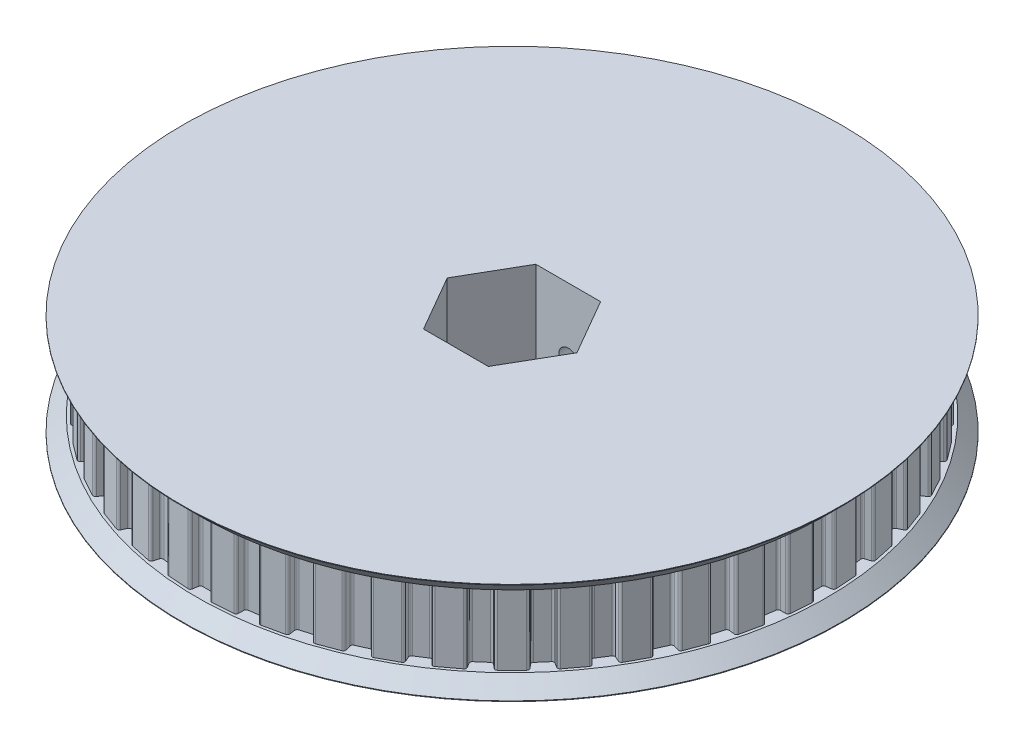
SolidWorks part; units mm, degrees
ref_plane "Front Plane" through (0, 0, 0) normal (0, 0, 1) x (1, 0, 0)
ref_plane "Top Plane" through (0, 0, 0) normal (0, 1, 0) x (1, 0, 0)
ref_plane "Right Plane" through (0, 0, 0) normal (1, 0, 0) x (0, 0, -1)
sketch "Sketch1" plane through (0, 0, 0) normal (0, 1, 0) x (1, 0, 0)
  line L0 (-1.778, 64.4158) -> (1.778, 64.4158) construction
  line L12 (-1.778, 64.4158) -> (-2.0983, 66.4224) construction
  line L13 (1.778, 64.4158) -> (2.0983, 66.4224) construction
  line L14 (2.0983, 66.4224) -> (-2.0983, 66.4224) construction
  line L15 (-2.0983, 66.4224) -> (-7.376, 66.045) construction
  line L16 (2.0983, 66.4224) -> (7.376, 66.045) construction
  line L17 (7.376, 66.045) -> (7.4074, 64.0132) construction
  line L18 (7.4074, 64.0132) -> (10.9272, 63.5071) construction
  line L19 (10.9272, 63.5071) -> (11.5298, 65.4477) construction
  line L20 (11.5298, 65.4477) -> (7.376, 66.045) construction
  line L21 (0, 64.4158) -> (0, 66.4224) construction
  line L22 (9.1673, 63.7602) -> (9.4529, 65.7464) construction
  line L105 (-1.3447, 64.4158) -> (1.3447, 64.4158)
  line L106 (1.8463, 64.8438) -> (2.0249, 65.9626)
  line L107 (2.5628, 66.3892) -> (6.9115, 66.0782)
  line L108 (7.3832, 65.5793) -> (7.4007, 64.4465)
  line L109 (7.8364, 63.9515) -> (10.4983, 63.5688)
  line L110 (11.0557, 63.921) -> (11.3917, 65.003)
  line L112 (9.4529, 65.7464) -> (10.0269, 69.7388) construction
  line L113 (0, 66.4224) -> (0, 66.7018) construction
  line L117 (-6.9115, 66.0782) -> (-2.5628, 66.3892)
  line L118 (-2.0249, 65.9626) -> (-1.8463, 64.8438)
  line L119 (28.6165, 58.217) -> (29.2437, 59.1605)
  line L120 (25.5362, 59.1533) -> (27.9824, 58.0361)
  line L121 (25.5599, 60.8428) -> (25.2576, 59.7509)
  line L122 (21.163, 62.978) -> (25.2479, 61.4544)
  line L123 (20.0401, 61.697) -> (20.5267, 62.7202)
  line L124 (16.8579, 62.1854) -> (19.4382, 61.4277)
  line L125 (16.6409, 63.8611) -> (16.4971, 62.7373)
  line L126 (11.9849, 65.3487) -> (16.245, 64.422)
  line L127 (43.859, 47.7966) -> (44.7266, 48.5252)
  line L128 (41.1672, 49.5628) -> (43.1996, 47.8017)
  line L129 (41.666, 51.1772) -> (41.0683, 50.2147)
  line L130 (38.0487, 54.4646) -> (41.5389, 51.8519)
  line L131 (36.6104, 53.5519) -> (37.3655, 54.3965)
  line L132 (33.6946, 54.917) -> (35.957, 53.4631)
  line L133 (33.9586, 56.586) -> (33.504, 55.5482)
  line L134 (29.9103, 59.3251) -> (33.7368, 57.2357)
  line L135 (55.5482, 33.504) -> (56.586, 33.9586)
  line L136 (53.4631, 35.957) -> (54.917, 33.6946)
  line L137 (54.3965, 37.3655) -> (53.5519, 36.6104)
  line L138 (51.8519, 41.5389) -> (54.4646, 38.0487)
  line L139 (50.2147, 41.0683) -> (51.1772, 41.666)
  line L140 (47.8017, 43.1996) -> (49.5628, 41.1672)
  line L141 (48.5252, 44.7266) -> (47.7966, 43.859)
  line L142 (45.4125, 48.4954) -> (48.4954, 45.4125)
  line L143 (62.7373, 16.4971) -> (63.8611, 16.6409)
  line L144 (61.4277, 19.4382) -> (62.1854, 16.8579)
  line L145 (62.7202, 20.5267) -> (61.697, 20.0401)
  line L146 (61.4544, 25.2479) -> (62.978, 21.163)
  line L147 (59.7509, 25.2576) -> (60.8428, 25.5599)
  line L148 (58.0361, 27.9824) -> (59.1533, 25.5362)
  line L149 (59.1605, 29.2437) -> (58.217, 28.6165)
  line L150 (57.2357, 33.7368) -> (59.3251, 29.9103)
  line L151 (64.8438, -1.8463) -> (65.9626, -2.0249)
  line L152 (64.4158, 1.3447) -> (64.4158, -1.3447)
  line L153 (65.9626, 2.0249) -> (64.8438, 1.8463)
  line L154 (66.0782, 6.9115) -> (66.3892, 2.5628)
  line L155 (64.4465, 7.4007) -> (65.5793, 7.3832)
  line L156 (63.5688, 10.4983) -> (63.9515, 7.8364)
  line L157 (65.003, 11.3917) -> (63.921, 11.0557)
  line L158 (64.422, 16.245) -> (65.3487, 11.9849)
  line L159 (61.697, -20.0401) -> (62.7202, -20.5267)
  line L160 (62.1854, -16.8579) -> (61.4277, -19.4382)
  line L161 (63.8611, -16.6409) -> (62.7373, -16.4971)
  line L162 (65.3487, -11.9849) -> (64.422, -16.245)
  line L163 (63.921, -11.0557) -> (65.003, -11.3917)
  line L164 (63.9515, -7.8364) -> (63.5688, -10.4983)
  line L165 (65.5793, -7.3832) -> (64.4465, -7.4007)
  line L166 (66.3892, -2.5628) -> (66.0782, -6.9115)
  line L167 (53.5519, -36.6104) -> (54.3965, -37.3655)
  line L168 (54.917, -33.6946) -> (53.4631, -35.957)
  line L169 (56.586, -33.9586) -> (55.5482, -33.504)
  line L170 (59.3251, -29.9103) -> (57.2357, -33.7368)
  line L171 (58.217, -28.6165) -> (59.1605, -29.2437)
  line L172 (59.1533, -25.5362) -> (58.0361, -27.9824)
  line L173 (60.8428, -25.5599) -> (59.7509, -25.2576)
  line L174 (62.978, -21.163) -> (61.4544, -25.2479)
  line L175 (41.0683, -50.2147) -> (41.666, -51.1772)
  line L176 (43.1996, -47.8017) -> (41.1672, -49.5628)
  line L177 (44.7266, -48.5252) -> (43.859, -47.7966)
  line L178 (48.4954, -45.4125) -> (45.4125, -48.4954)
  line L179 (47.7966, -43.859) -> (48.5252, -44.7266)
  line L180 (49.5628, -41.1672) -> (47.8017, -43.1996)
  line L181 (51.1772, -41.666) -> (50.2147, -41.0683)
  line L182 (54.4646, -38.0487) -> (51.8519, -41.5389)
  line L183 (25.2576, -59.7509) -> (25.5599, -60.8428)
  line L184 (27.9824, -58.0361) -> (25.5362, -59.1533)
  line L185 (29.2437, -59.1605) -> (28.6165, -58.217)
  line L186 (33.7368, -57.2357) -> (29.9103, -59.3251)
  line L187 (33.504, -55.5482) -> (33.9586, -56.586)
  line L188 (35.957, -53.4631) -> (33.6946, -54.917)
  line L189 (37.3655, -54.3965) -> (36.6104, -53.5519)
  line L190 (41.5389, -51.8519) -> (38.0487, -54.4646)
  line L191 (7.4007, -64.4465) -> (7.3832, -65.5793)
  line L192 (10.4983, -63.5688) -> (7.8364, -63.9515)
  line L193 (11.3917, -65.003) -> (11.0557, -63.921)
  line L194 (16.245, -64.422) -> (11.9849, -65.3487)
  line L195 (16.4971, -62.7373) -> (16.6409, -63.8611)
  line L196 (19.4382, -61.4277) -> (16.8579, -62.1854)
  line L197 (20.5267, -62.7202) -> (20.0401, -61.697)
  line L198 (25.2479, -61.4544) -> (21.163, -62.978)
  line L199 (-11.0557, -63.921) -> (-11.3917, -65.003)
  line L200 (-7.8364, -63.9515) -> (-10.4983, -63.5688)
  line L201 (-7.3832, -65.5793) -> (-7.4007, -64.4465)
  line L202 (-2.5628, -66.3892) -> (-6.9115, -66.0782)
  line L203 (-1.8463, -64.8438) -> (-2.0249, -65.9626)
  line L204 (1.3447, -64.4158) -> (-1.3447, -64.4158)
  line L205 (2.0249, -65.9626) -> (1.8463, -64.8438)
  line L206 (6.9115, -66.0782) -> (2.5628, -66.3892)
  line L207 (-28.6165, -58.217) -> (-29.2437, -59.1605)
  line L208 (-25.5362, -59.1533) -> (-27.9824, -58.0361)
  line L209 (-25.5599, -60.8428) -> (-25.2576, -59.7509)
  line L210 (-21.163, -62.978) -> (-25.2479, -61.4544)
  line L211 (-20.0401, -61.697) -> (-20.5267, -62.7202)
  line L212 (-16.8579, -62.1854) -> (-19.4382, -61.4277)
  line L213 (-16.6409, -63.8611) -> (-16.4971, -62.7373)
  line L214 (-11.9849, -65.3487) -> (-16.245, -64.422)
  line L215 (-43.859, -47.7966) -> (-44.7266, -48.5252)
  line L216 (-41.1672, -49.5628) -> (-43.1996, -47.8017)
  line L217 (-41.666, -51.1772) -> (-41.0683, -50.2147)
  line L218 (-38.0487, -54.4646) -> (-41.5389, -51.8519)
  line L219 (-36.6104, -53.5519) -> (-37.3655, -54.3965)
  line L220 (-33.6946, -54.917) -> (-35.957, -53.4631)
  line L221 (-33.9586, -56.586) -> (-33.504, -55.5482)
  line L222 (-29.9103, -59.3251) -> (-33.7368, -57.2357)
  line L223 (-55.5482, -33.504) -> (-56.586, -33.9586)
  line L224 (-53.4631, -35.957) -> (-54.917, -33.6946)
  line L225 (-54.3965, -37.3655) -> (-53.5519, -36.6104)
  line L226 (-51.8519, -41.5389) -> (-54.4646, -38.0487)
  line L227 (-50.2147, -41.0683) -> (-51.1772, -41.666)
  line L228 (-47.8017, -43.1996) -> (-49.5628, -41.1672)
  line L229 (-48.5252, -44.7266) -> (-47.7966, -43.859)
  line L230 (-45.4125, -48.4954) -> (-48.4954, -45.4125)
  line L231 (-62.7373, -16.4971) -> (-63.8611, -16.6409)
  line L232 (-61.4277, -19.4382) -> (-62.1854, -16.8579)
  line L233 (-62.7202, -20.5267) -> (-61.697, -20.0401)
  line L234 (-61.4544, -25.2479) -> (-62.978, -21.163)
  line L235 (-59.7509, -25.2576) -> (-60.8428, -25.5599)
  line L236 (-58.0361, -27.9824) -> (-59.1533, -25.5362)
  line L237 (-59.1605, -29.2437) -> (-58.217, -28.6165)
  line L238 (-57.2357, -33.7368) -> (-59.3251, -29.9103)
  line L239 (-64.8438, 1.8463) -> (-65.9626, 2.0249)
  line L240 (-64.4158, -1.3447) -> (-64.4158, 1.3447)
  line L241 (-65.9626, -2.0249) -> (-64.8438, -1.8463)
  line L242 (-66.0782, -6.9115) -> (-66.3892, -2.5628)
  line L243 (-64.4465, -7.4007) -> (-65.5793, -7.3832)
  line L244 (-63.5688, -10.4983) -> (-63.9515, -7.8364)
  line L245 (-65.003, -11.3917) -> (-63.921, -11.0557)
  line L246 (-64.422, -16.245) -> (-65.3487, -11.9849)
  line L247 (-61.697, 20.0401) -> (-62.7202, 20.5267)
  line L248 (-62.1854, 16.8579) -> (-61.4277, 19.4382)
  line L249 (-63.8611, 16.6409) -> (-62.7373, 16.4971)
  line L250 (-65.3487, 11.9849) -> (-64.422, 16.245)
  line L251 (-63.921, 11.0557) -> (-65.003, 11.3917)
  line L252 (-63.9515, 7.8364) -> (-63.5688, 10.4983)
  line L253 (-65.5793, 7.3832) -> (-64.4465, 7.4007)
  line L254 (-66.3892, 2.5628) -> (-66.0782, 6.9115)
  line L255 (-53.5519, 36.6104) -> (-54.3965, 37.3655)
  line L256 (-54.917, 33.6946) -> (-53.4631, 35.957)
  line L257 (-56.586, 33.9586) -> (-55.5482, 33.504)
  line L258 (-59.3251, 29.9103) -> (-57.2357, 33.7368)
  line L259 (-58.217, 28.6165) -> (-59.1605, 29.2437)
  line L260 (-59.1533, 25.5362) -> (-58.0361, 27.9824)
  line L261 (-60.8428, 25.5599) -> (-59.7509, 25.2576)
  line L262 (-62.978, 21.163) -> (-61.4544, 25.2479)
  line L263 (-41.0683, 50.2147) -> (-41.666, 51.1772)
  line L264 (-43.1996, 47.8017) -> (-41.1672, 49.5628)
  line L265 (-44.7266, 48.5252) -> (-43.859, 47.7966)
  line L266 (-48.4954, 45.4125) -> (-45.4125, 48.4954)
  line L267 (-47.7966, 43.859) -> (-48.5252, 44.7266)
  line L268 (-49.5628, 41.1672) -> (-47.8017, 43.1996)
  line L269 (-51.1772, 41.666) -> (-50.2147, 41.0683)
  line L270 (-54.4646, 38.0487) -> (-51.8519, 41.5389)
  line L271 (-25.2576, 59.7509) -> (-25.5599, 60.8428)
  line L272 (-27.9824, 58.0361) -> (-25.5362, 59.1533)
  line L273 (-29.2437, 59.1605) -> (-28.6165, 58.217)
  line L274 (-33.7368, 57.2357) -> (-29.9103, 59.3251)
  line L275 (-33.504, 55.5482) -> (-33.9586, 56.586)
  line L276 (-35.957, 53.4631) -> (-33.6946, 54.917)
  line L277 (-37.3655, 54.3965) -> (-36.6104, 53.5519)
  line L278 (-41.5389, 51.8519) -> (-38.0487, 54.4646)
  line L279 (-7.4007, 64.4465) -> (-7.3832, 65.5793)
  line L280 (-10.4983, 63.5688) -> (-7.8364, 63.9515)
  line L281 (-11.3917, 65.003) -> (-11.0557, 63.921)
  line L282 (-16.245, 64.422) -> (-11.9849, 65.3487)
  line L283 (-16.4971, 62.7373) -> (-16.6409, 63.8611)
  line L284 (-19.4382, 61.4277) -> (-16.8579, 62.1854)
  line L285 (-20.5267, 62.7202) -> (-20.0401, 61.697)
  line L286 (-25.2479, 61.4544) -> (-21.163, 62.978)
  line L287 (-7.376, 66.045) -> (-7.4074, 64.0132) construction
  line L288 (-10.4983, 63.5688) -> (-7.4074, 64.0132) construction
  arc A0 (0, 64.4158) -> (9.1673, 63.7602) centre (0, 0) cw construction
  arc A1 (27.9824, 58.0361) -> (28.6165, 58.217) centre (28.1935, 58.4982) ccw
  arc A2 (25.2576, 59.7509) -> (25.5362, 59.1533) centre (25.7472, 59.6154) ccw
  arc A3 (25.2479, 61.4544) -> (25.5599, 60.8428) centre (25.0704, 60.9784) cw
  arc A4 (20.5267, 62.7202) -> (21.163, 62.978) centre (20.9854, 62.502) cw
  arc A5 (20.0401, 61.697) -> (19.4382, 61.4277) centre (19.5813, 61.9151) cw
  arc A6 (16.8579, 62.1854) -> (16.4971, 62.7373) centre (17.001, 62.6728) cw
  arc A7 (16.245, 64.422) -> (16.6409, 63.8611) centre (16.1371, 63.9256) cw
  arc A8 (18.148, 61.8065) -> (26.7593, 58.5947) centre (0, 0) cw construction
  arc A9 (43.1996, 47.8017) -> (43.859, 47.7966) centre (43.5323, 48.1856) ccw
  arc A10 (41.0683, 50.2147) -> (41.1672, 49.5628) centre (41.4998, 49.9467) ccw
  arc A87 (10.4983, 63.5688) -> (11.0557, 63.921) centre (10.5706, 64.0716) ccw
  arc A88 (7.4007, 64.4465) -> (7.8364, 63.9515) centre (7.9087, 64.4544) ccw
  arc A89 (6.9115, 66.0782) -> (7.3832, 65.5793) centre (6.8752, 65.5715) cw
  arc A90 (2.0249, 65.9626) -> (2.5628, 66.3892) centre (2.5265, 65.8825) cw
  arc A91 (1.8463, 64.8438) -> (1.3447, 64.4158) centre (1.3447, 64.9238) cw
  arc A94 (0, 66.7018) -> (9.4927, 66.0229) centre (0, 0) cw construction
  arc A96 (-1.3447, 64.4158) -> (-1.8463, 64.8438) centre (-1.3447, 64.9238) cw
  arc A97 (-2.5628, 66.3892) -> (-2.0249, 65.9626) centre (-2.5265, 65.8825) cw
  arc A98 (41.5389, 51.8519) -> (41.666, 51.1772) centre (41.2344, 51.4452) cw
  arc A99 (37.3655, 54.3965) -> (38.0487, 54.4646) centre (37.7442, 54.0579) cw
  arc A100 (36.6104, 53.5519) -> (35.957, 53.4631) centre (36.2317, 53.8904) cw
  arc A101 (33.6946, 54.917) -> (33.504, 55.5482) centre (33.9693, 55.3444) cw
  arc A102 (33.7368, 57.2357) -> (33.9586, 56.586) centre (33.4933, 56.7898) cw
  arc A103 (34.8258, 54.1901) -> (42.1834, 48.6822) centre (0, 0) cw construction
  arc A104 (54.917, 33.6946) -> (55.5482, 33.504) centre (55.3444, 33.9693) ccw
  arc A105 (53.5519, 36.6104) -> (53.4631, 35.957) centre (53.8904, 36.2317) ccw
  arc A106 (54.4646, 38.0487) -> (54.3965, 37.3655) centre (54.0579, 37.7442) cw
  arc A107 (51.1772, 41.666) -> (51.8519, 41.5389) centre (51.4452, 41.2344) cw
  arc A108 (50.2147, 41.0683) -> (49.5628, 41.1672) centre (49.9467, 41.4998) cw
  arc A109 (47.8017, 43.1996) -> (47.7966, 43.859) centre (48.1856, 43.5323) cw
  arc A110 (48.4954, 45.4125) -> (48.5252, 44.7266) centre (48.1362, 45.0533) cw
  arc A111 (48.6822, 42.1834) -> (54.1901, 34.8258) centre (0, 0) cw construction
  arc A112 (62.1854, 16.8579) -> (62.7373, 16.4971) centre (62.6728, 17.001) ccw
  arc A113 (61.697, 20.0401) -> (61.4277, 19.4382) centre (61.9151, 19.5813) ccw
  arc A114 (62.978, 21.163) -> (62.7202, 20.5267) centre (62.502, 20.9854) cw
  arc A115 (60.8428, 25.5599) -> (61.4544, 25.2479) centre (60.9784, 25.0704) cw
  arc A116 (59.7509, 25.2576) -> (59.1533, 25.5362) centre (59.6154, 25.7472) cw
  arc A117 (58.0361, 27.9824) -> (58.217, 28.6165) centre (58.4982, 28.1935) cw
  arc A118 (59.3251, 29.9103) -> (59.1605, 29.2437) centre (58.8793, 29.6668) cw
  arc A119 (58.5947, 26.7593) -> (61.8065, 18.148) centre (0, 0) cw construction
  arc A120 (64.4158, -1.3447) -> (64.8438, -1.8463) centre (64.9238, -1.3447) ccw
  arc A121 (64.8438, 1.8463) -> (64.4158, 1.3447) centre (64.9238, 1.3447) ccw
  arc A122 (66.3892, 2.5628) -> (65.9626, 2.0249) centre (65.8825, 2.5265) cw
  arc A123 (65.5793, 7.3832) -> (66.0782, 6.9115) centre (65.5715, 6.8752) cw
  arc A124 (64.4465, 7.4007) -> (63.9515, 7.8364) centre (64.4544, 7.9087) cw
  arc A125 (63.5688, 10.4983) -> (63.921, 11.0557) centre (64.0716, 10.5706) cw
  arc A126 (65.3487, 11.9849) -> (65.003, 11.3917) centre (64.8524, 11.8769) cw
  arc A127 (63.7602, 9.1673) -> (64.4158, 0) centre (0, 0) cw construction
  arc A128 (61.4277, -19.4382) -> (61.697, -20.0401) centre (61.9151, -19.5813) ccw
  arc A129 (62.7373, -16.4971) -> (62.1854, -16.8579) centre (62.6728, -17.001) ccw
  arc A130 (64.422, -16.245) -> (63.8611, -16.6409) centre (63.9256, -16.1371) cw
  arc A131 (65.003, -11.3917) -> (65.3487, -11.9849) centre (64.8524, -11.8769) cw
  arc A132 (63.921, -11.0557) -> (63.5688, -10.4983) centre (64.0716, -10.5706) cw
  arc A133 (63.9515, -7.8364) -> (64.4465, -7.4007) centre (64.4544, -7.9087) cw
  arc A134 (66.0782, -6.9115) -> (65.5793, -7.3832) centre (65.5715, -6.8752) cw
  arc A135 (63.7602, -9.1673) -> (61.8065, -18.148) centre (0, 0) cw construction
  arc A136 (53.4631, -35.957) -> (53.5519, -36.6104) centre (53.8904, -36.2317) ccw
  arc A137 (55.5482, -33.504) -> (54.917, -33.6946) centre (55.3444, -33.9693) ccw
  arc A138 (57.2357, -33.7368) -> (56.586, -33.9586) centre (56.7898, -33.4933) cw
  arc A139 (59.1605, -29.2437) -> (59.3251, -29.9103) centre (58.8793, -29.6668) cw
  arc A140 (58.217, -28.6165) -> (58.0361, -27.9824) centre (58.4982, -28.1935) cw
  arc A141 (59.1533, -25.5362) -> (59.7509, -25.2576) centre (59.6154, -25.7472) cw
  arc A142 (61.4544, -25.2479) -> (60.8428, -25.5599) centre (60.9784, -25.0704) cw
  arc A143 (58.5947, -26.7593) -> (54.1901, -34.8258) centre (0, 0) cw construction
  arc A144 (41.1672, -49.5628) -> (41.0683, -50.2147) centre (41.4998, -49.9467) ccw
  arc A145 (43.859, -47.7966) -> (43.1996, -47.8017) centre (43.5323, -48.1856) ccw
  arc A146 (45.4125, -48.4954) -> (44.7266, -48.5252) centre (45.0533, -48.1362) cw
  arc A147 (48.5252, -44.7266) -> (48.4954, -45.4125) centre (48.1362, -45.0533) cw
  arc A148 (47.7966, -43.859) -> (47.8017, -43.1996) centre (48.1856, -43.5323) cw
  arc A149 (49.5628, -41.1672) -> (50.2147, -41.0683) centre (49.9467, -41.4998) cw
  arc A150 (51.8519, -41.5389) -> (51.1772, -41.666) centre (51.4452, -41.2344) cw
  arc A151 (48.6822, -42.1834) -> (42.1834, -48.6822) centre (0, 0) cw construction
  arc A152 (25.5362, -59.1533) -> (25.2576, -59.7509) centre (25.7472, -59.6154) ccw
  arc A153 (28.6165, -58.217) -> (27.9824, -58.0361) centre (28.1935, -58.4982) ccw
  arc A154 (29.9103, -59.3251) -> (29.2437, -59.1605) centre (29.6668, -58.8793) cw
  arc A155 (33.9586, -56.586) -> (33.7368, -57.2357) centre (33.4933, -56.7898) cw
  arc A156 (33.504, -55.5482) -> (33.6946, -54.917) centre (33.9693, -55.3444) cw
  arc A157 (35.957, -53.4631) -> (36.6104, -53.5519) centre (36.2317, -53.8904) cw
  arc A158 (38.0487, -54.4646) -> (37.3655, -54.3965) centre (37.7442, -54.0579) cw
  arc A159 (34.8258, -54.1901) -> (26.7593, -58.5947) centre (0, 0) cw construction
  arc A160 (7.8364, -63.9515) -> (7.4007, -64.4465) centre (7.9087, -64.4544) ccw
  arc A161 (11.0557, -63.921) -> (10.4983, -63.5688) centre (10.5706, -64.0716) ccw
  arc A162 (11.9849, -65.3487) -> (11.3917, -65.003) centre (11.8769, -64.8524) cw
  arc A163 (16.6409, -63.8611) -> (16.245, -64.422) centre (16.1371, -63.9256) cw
  arc A164 (16.4971, -62.7373) -> (16.8579, -62.1854) centre (17.001, -62.6728) cw
  arc A165 (19.4382, -61.4277) -> (20.0401, -61.697) centre (19.5813, -61.9151) cw
  arc A166 (21.163, -62.978) -> (20.5267, -62.7202) centre (20.9854, -62.502) cw
  arc A167 (18.148, -61.8065) -> (9.1673, -63.7602) centre (0, 0) cw construction
  arc A168 (-10.4983, -63.5688) -> (-11.0557, -63.921) centre (-10.5706, -64.0716) ccw
  arc A169 (-7.4007, -64.4465) -> (-7.8364, -63.9515) centre (-7.9087, -64.4544) ccw
  arc A170 (-6.9115, -66.0782) -> (-7.3832, -65.5793) centre (-6.8752, -65.5715) cw
  arc A171 (-2.0249, -65.9626) -> (-2.5628, -66.3892) centre (-2.5265, -65.8825) cw
  arc A172 (-1.8463, -64.8438) -> (-1.3447, -64.4158) centre (-1.3447, -64.9238) cw
  arc A173 (1.3447, -64.4158) -> (1.8463, -64.8438) centre (1.3447, -64.9238) cw
  arc A174 (2.5628, -66.3892) -> (2.0249, -65.9626) centre (2.5265, -65.8825) cw
  arc A175 (0, -64.4158) -> (-9.1673, -63.7602) centre (0, 0) cw construction
  arc A176 (-27.9824, -58.0361) -> (-28.6165, -58.217) centre (-28.1935, -58.4982) ccw
  arc A177 (-25.2576, -59.7509) -> (-25.5362, -59.1533) centre (-25.7472, -59.6154) ccw
  arc A178 (-25.2479, -61.4544) -> (-25.5599, -60.8428) centre (-25.0704, -60.9784) cw
  arc A179 (-20.5267, -62.7202) -> (-21.163, -62.978) centre (-20.9854, -62.502) cw
  arc A180 (-20.0401, -61.697) -> (-19.4382, -61.4277) centre (-19.5813, -61.9151) cw
  arc A181 (-16.8579, -62.1854) -> (-16.4971, -62.7373) centre (-17.001, -62.6728) cw
  arc A182 (-16.245, -64.422) -> (-16.6409, -63.8611) centre (-16.1371, -63.9256) cw
  arc A183 (-18.148, -61.8065) -> (-26.7593, -58.5947) centre (0, 0) cw construction
  arc A184 (-43.1996, -47.8017) -> (-43.859, -47.7966) centre (-43.5323, -48.1856) ccw
  arc A185 (-41.0683, -50.2147) -> (-41.1672, -49.5628) centre (-41.4998, -49.9467) ccw
  arc A186 (-41.5389, -51.8519) -> (-41.666, -51.1772) centre (-41.2344, -51.4452) cw
  arc A187 (-37.3655, -54.3965) -> (-38.0487, -54.4646) centre (-37.7442, -54.0579) cw
  arc A188 (-36.6104, -53.5519) -> (-35.957, -53.4631) centre (-36.2317, -53.8904) cw
  arc A189 (-33.6946, -54.917) -> (-33.504, -55.5482) centre (-33.9693, -55.3444) cw
  arc A190 (-33.7368, -57.2357) -> (-33.9586, -56.586) centre (-33.4933, -56.7898) cw
  arc A191 (-34.8258, -54.1901) -> (-42.1834, -48.6822) centre (0, 0) cw construction
  arc A192 (-54.917, -33.6946) -> (-55.5482, -33.504) centre (-55.3444, -33.9693) ccw
  arc A193 (-53.5519, -36.6104) -> (-53.4631, -35.957) centre (-53.8904, -36.2317) ccw
  arc A194 (-54.4646, -38.0487) -> (-54.3965, -37.3655) centre (-54.0579, -37.7442) cw
  arc A195 (-51.1772, -41.666) -> (-51.8519, -41.5389) centre (-51.4452, -41.2344) cw
  arc A196 (-50.2147, -41.0683) -> (-49.5628, -41.1672) centre (-49.9467, -41.4998) cw
  arc A197 (-47.8017, -43.1996) -> (-47.7966, -43.859) centre (-48.1856, -43.5323) cw
  arc A198 (-48.4954, -45.4125) -> (-48.5252, -44.7266) centre (-48.1362, -45.0533) cw
  arc A199 (-48.6822, -42.1834) -> (-54.1901, -34.8258) centre (0, 0) cw construction
  arc A200 (-62.1854, -16.8579) -> (-62.7373, -16.4971) centre (-62.6728, -17.001) ccw
  arc A201 (-61.697, -20.0401) -> (-61.4277, -19.4382) centre (-61.9151, -19.5813) ccw
  arc A202 (-62.978, -21.163) -> (-62.7202, -20.5267) centre (-62.502, -20.9854) cw
  arc A203 (-60.8428, -25.5599) -> (-61.4544, -25.2479) centre (-60.9784, -25.0704) cw
  arc A204 (-59.7509, -25.2576) -> (-59.1533, -25.5362) centre (-59.6154, -25.7472) cw
  arc A205 (-58.0361, -27.9824) -> (-58.217, -28.6165) centre (-58.4982, -28.1935) cw
  arc A206 (-59.3251, -29.9103) -> (-59.1605, -29.2437) centre (-58.8793, -29.6668) cw
  arc A207 (-58.5947, -26.7593) -> (-61.8065, -18.148) centre (0, 0) cw construction
  arc A208 (-64.4158, 1.3447) -> (-64.8438, 1.8463) centre (-64.9238, 1.3447) ccw
  arc A209 (-64.8438, -1.8463) -> (-64.4158, -1.3447) centre (-64.9238, -1.3447) ccw
  arc A210 (-66.3892, -2.5628) -> (-65.9626, -2.0249) centre (-65.8825, -2.5265) cw
  arc A211 (-65.5793, -7.3832) -> (-66.0782, -6.9115) centre (-65.5715, -6.8752) cw
  arc A212 (-64.4465, -7.4007) -> (-63.9515, -7.8364) centre (-64.4544, -7.9087) cw
  arc A213 (-63.5688, -10.4983) -> (-63.921, -11.0557) centre (-64.0716, -10.5706) cw
  arc A214 (-65.3487, -11.9849) -> (-65.003, -11.3917) centre (-64.8524, -11.8769) cw
  arc A215 (-63.7602, -9.1673) -> (-64.4158, 0) centre (0, 0) cw construction
  arc A216 (-61.4277, 19.4382) -> (-61.697, 20.0401) centre (-61.9151, 19.5813) ccw
  arc A217 (-62.7373, 16.4971) -> (-62.1854, 16.8579) centre (-62.6728, 17.001) ccw
  arc A218 (-64.422, 16.245) -> (-63.8611, 16.6409) centre (-63.9256, 16.1371) cw
  arc A219 (-65.003, 11.3917) -> (-65.3487, 11.9849) centre (-64.8524, 11.8769) cw
  arc A220 (-63.921, 11.0557) -> (-63.5688, 10.4983) centre (-64.0716, 10.5706) cw
  arc A221 (-63.9515, 7.8364) -> (-64.4465, 7.4007) centre (-64.4544, 7.9087) cw
  arc A222 (-66.0782, 6.9115) -> (-65.5793, 7.3832) centre (-65.5715, 6.8752) cw
  arc A223 (-63.7602, 9.1673) -> (-61.8065, 18.148) centre (0, 0) cw construction
  arc A224 (-53.4631, 35.957) -> (-53.5519, 36.6104) centre (-53.8904, 36.2317) ccw
  arc A225 (-55.5482, 33.504) -> (-54.917, 33.6946) centre (-55.3444, 33.9693) ccw
  arc A226 (-57.2357, 33.7368) -> (-56.586, 33.9586) centre (-56.7898, 33.4933) cw
  arc A227 (-59.1605, 29.2437) -> (-59.3251, 29.9103) centre (-58.8793, 29.6668) cw
  arc A228 (-58.217, 28.6165) -> (-58.0361, 27.9824) centre (-58.4982, 28.1935) cw
  arc A229 (-59.1533, 25.5362) -> (-59.7509, 25.2576) centre (-59.6154, 25.7472) cw
  arc A230 (-61.4544, 25.2479) -> (-60.8428, 25.5599) centre (-60.9784, 25.0704) cw
  arc A231 (-58.5947, 26.7593) -> (-54.1901, 34.8258) centre (0, 0) cw construction
  arc A232 (-41.1672, 49.5628) -> (-41.0683, 50.2147) centre (-41.4998, 49.9467) ccw
  arc A233 (-43.859, 47.7966) -> (-43.1996, 47.8017) centre (-43.5323, 48.1856) ccw
  arc A234 (-45.4125, 48.4954) -> (-44.7266, 48.5252) centre (-45.0533, 48.1362) cw
  arc A235 (-48.5252, 44.7266) -> (-48.4954, 45.4125) centre (-48.1362, 45.0533) cw
  arc A236 (-47.7966, 43.859) -> (-47.8017, 43.1996) centre (-48.1856, 43.5323) cw
  arc A237 (-49.5628, 41.1672) -> (-50.2147, 41.0683) centre (-49.9467, 41.4998) cw
  arc A238 (-51.8519, 41.5389) -> (-51.1772, 41.666) centre (-51.4452, 41.2344) cw
  arc A239 (-48.6822, 42.1834) -> (-42.1834, 48.6822) centre (0, 0) cw construction
  arc A240 (-25.5362, 59.1533) -> (-25.2576, 59.7509) centre (-25.7472, 59.6154) ccw
  arc A241 (-28.6165, 58.217) -> (-27.9824, 58.0361) centre (-28.1935, 58.4982) ccw
  arc A242 (-29.9103, 59.3251) -> (-29.2437, 59.1605) centre (-29.6668, 58.8793) cw
  arc A243 (-33.9586, 56.586) -> (-33.7368, 57.2357) centre (-33.4933, 56.7898) cw
  arc A244 (-33.504, 55.5482) -> (-33.6946, 54.917) centre (-33.9693, 55.3444) cw
  arc A245 (-35.957, 53.4631) -> (-36.6104, 53.5519) centre (-36.2317, 53.8904) cw
  arc A246 (-38.0487, 54.4646) -> (-37.3655, 54.3965) centre (-37.7442, 54.0579) cw
  arc A247 (-34.8258, 54.1901) -> (-26.7593, 58.5947) centre (0, 0) cw construction
  arc A248 (-7.8364, 63.9515) -> (-7.4007, 64.4465) centre (-7.9087, 64.4544) ccw
  arc A249 (-11.0557, 63.921) -> (-10.4983, 63.5688) centre (-10.5706, 64.0716) ccw
  arc A250 (-11.9849, 65.3487) -> (-11.3917, 65.003) centre (-11.8769, 64.8524) cw
  arc A251 (-16.6409, 63.8611) -> (-16.245, 64.422) centre (-16.1371, 63.9256) cw
  arc A252 (-16.4971, 62.7373) -> (-16.8579, 62.1854) centre (-17.001, 62.6728) cw
  arc A253 (-19.4382, 61.4277) -> (-20.0401, 61.697) centre (-19.5813, 61.9151) cw
  arc A254 (-21.163, 62.978) -> (-20.5267, 62.7202) centre (-20.9854, 62.502) cw
  arc A255 (-18.148, 61.8065) -> (-9.1673, 63.7602) centre (0, 0) cw construction
  arc A256 (29.2437, 59.1605) -> (29.9103, 59.3251) centre (29.6668, 58.8793) cw
  arc A257 (44.7266, 48.5252) -> (45.4125, 48.4954) centre (45.0533, 48.1362) cw
  arc A258 (56.586, 33.9586) -> (57.2357, 33.7368) centre (56.7898, 33.4933) cw
  arc A259 (63.8611, 16.6409) -> (64.422, 16.245) centre (63.9256, 16.1371) cw
  arc A260 (65.9626, -2.0249) -> (66.3892, -2.5628) centre (65.8825, -2.5265) cw
  arc A261 (62.7202, -20.5267) -> (62.978, -21.163) centre (62.502, -20.9854) cw
  arc A262 (54.3965, -37.3655) -> (54.4646, -38.0487) centre (54.0579, -37.7442) cw
  arc A263 (41.666, -51.1772) -> (41.5389, -51.8519) centre (41.2344, -51.4452) cw
  arc A264 (25.5599, -60.8428) -> (25.2479, -61.4544) centre (25.0704, -60.9784) cw
  arc A265 (7.3832, -65.5793) -> (6.9115, -66.0782) centre (6.8752, -65.5715) cw
  arc A266 (-11.3917, -65.003) -> (-11.9849, -65.3487) centre (-11.8769, -64.8524) cw
  arc A267 (-29.2437, -59.1605) -> (-29.9103, -59.3251) centre (-29.6668, -58.8793) cw
  arc A268 (-44.7266, -48.5252) -> (-45.4125, -48.4954) centre (-45.0533, -48.1362) cw
  arc A269 (-56.586, -33.9586) -> (-57.2357, -33.7368) centre (-56.7898, -33.4933) cw
  arc A270 (-63.8611, -16.6409) -> (-64.422, -16.245) centre (-63.9256, -16.1371) cw
  arc A271 (-65.9626, 2.0249) -> (-66.3892, 2.5628) centre (-65.8825, 2.5265) cw
  arc A272 (-62.7202, 20.5267) -> (-62.978, 21.163) centre (-62.502, 20.9854) cw
  arc A273 (-54.3965, 37.3655) -> (-54.4646, 38.0487) centre (-54.0579, 37.7442) cw
  arc A274 (-41.666, 51.1772) -> (-41.5389, 51.8519) centre (-41.2344, 51.4452) cw
  arc A275 (-25.5599, 60.8428) -> (-25.2479, 61.4544) centre (-25.0704, 60.9784) cw
  arc A276 (-6.9115, 66.0782) -> (-7.3832, 65.5793) centre (-6.8752, 65.5715) ccw
  arc A277 (11.9849, 65.3487) -> (11.3917, 65.003) centre (11.8769, 64.8524) ccw
  point P13 (9.4927, 69.8156)
  point P589 (9.4168, 66.1352)
  dimension "D18" = 0.508
  dimension "D6" = 0.508
  dimension "D7" = 0.508
  dimension "D2" = 2.0066
  dimension "D3" = 2.032
  dimension "D4" = 2.286
  dimension "D16" = 9.525
  dimension "D5" = 22
extrude "Boss-Extrude1" add sketch "Sketch1" along normal blind 15.24
sketch "Sketch3" plane through (0, 0, 0) normal (0, 1, 0) x (1, 0, 0)
  line L0 (69.4749, 11.0458) -> (70.3397, -1.046) construction
  line L1 (66.3892, 2.5628) -> (66.0782, 6.9115) construction
  circle A0 centre (0, 0) radius 70.0859
  point P5 (69.9073, 4.9999)
  dimension "D1" = 3.683
  dimension "D2" = 12.1227
extrude "Boss-Extrude2" add sketch "Sketch3" along normal blind 3.175 from surface at 15.24 starting at face at (0, 15.24, 0)
sketch "Sketch4" plane through (0, 0, 0) normal (0, -1, 0) x (1, 0, 0)
  circle A0 centre (0, 0) radius 70.0859
  circle A1 centre (0, 0) radius 70.0859 construction
extrude "Boss-Extrude3" add sketch "Sketch4" along normal blind 3.175
chamfer "Chamfer1" distance 3.048 angle 45 1 edges at (0, 15.24, -70.0859)
chamfer "Chamfer2" distance 3.048 angle 45 1 edges at (0, 0, -70.0859)
sketch "Sketch5" plane through (0, -3.175, 0) normal (0, -1, 0) x (1, 0, 0)
  circle A0 centre (0, 0) radius 15.875
  dimension "D1" = 31.75
extrude "Boss-Extrude4" add sketch "Sketch5" along normal blind 6.35
sketch "Sketch13" plane through (0, -9.525, 0) normal (0, -1, 0) x (1, 0, 0)
  line L0 (-6.8924, 11.938) -> (6.8924, 11.938)
  line L1 (6.8924, 11.938) -> (13.7848, 0)
  line L2 (13.7848, 0) -> (6.8924, -11.938)
  line L3 (6.8924, -11.938) -> (-6.8924, -11.938)
  line L4 (-6.8924, -11.938) -> (-13.7848, 0)
  line L5 (-13.7848, 0) -> (-6.8924, 11.938)
  line L6 (13.7848, 0) -> (-13.7848, 0) construction
  line L7 (6.8924, -11.938) -> (-6.8924, 11.938) construction
  line L8 (6.8924, 11.938) -> (-6.8924, -11.938) construction
  point P7 (0, 0)
  point P9 (-5.1752, -8.9637)
  dimension "D1" = 23.876
extrude "Cut-Extrude4" cut sketch "Sketch13" against normal through all
ref_plane "Plane3" through (0, 0, 0) normal (0, 0, -1) x (-1, 0, 0)
sketch "Sketch10" plane through (0, 0, 0) normal (0, 0, -1) x (-1, 0, 0)
  line L1 (0, 4.445) -> (0, 18.415)
  line L3 (0, 4.445) -> (0, -9.525)
  line L5 (6.8924, 18.415) -> (-6.8924, 18.415) construction
  line L6 (-15.875, -9.525) -> (15.875, -9.525) construction
  circle A0 centre (0, 4.445) radius 1.9844
  point P2 (0, 7.62)
  point P3 (0, 0)
  point P8 (0, 0)
  dimension "D1" = 3.9688
extrude "Cut-Extrude3" cut sketch "Sketch10" along normal through all contours A0
equation "\"D1@Chamfer1\"=0.12"
equation "\"D1@Chamfer2\"=0.12"
equation "\"D16@Sketch1\"=3/8"
equation "\"D1@Sketch3\"=1/8+0.02"
